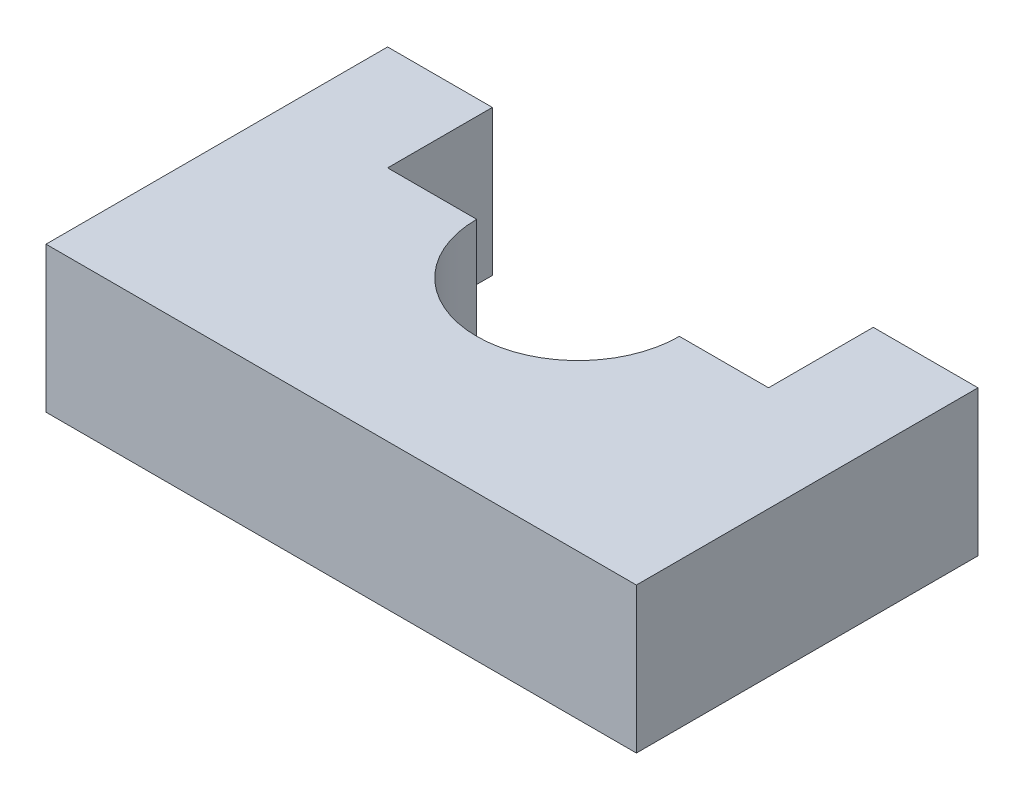
SolidWorks part; units mm, degrees
ref_plane "Front Plane" through (0, 0, 0) normal (0, 0, 1) x (1, 0, 0)
ref_plane "Top Plane" through (0, 0, 0) normal (0, 1, 0) x (1, 0, 0)
ref_plane "Right Plane" through (0, 0, 0) normal (1, 0, 0) x (0, 0, -1)
sketch "Sketch4" plane through (0, 0, 0) normal (0, 1, 0) x (1, 0, 0)
  line L0 (-30.4225, 0) -> (30.4225, 0)
  line L1 (30.4225, 0) -> (30.4225, 35.2066)
  line L3 (-30.4225, 0) -> (-30.4225, 35.2066)
  line L4 (-30.4225, 35.2066) -> (-19.6274, 35.2066)
  line L5 (30.4225, 35.2066) -> (19.6274, 35.2066)
  line L6 (-19.6274, 35.2066) -> (-19.6274, 24.4116)
  line L7 (-19.6274, 24.4116) -> (-10.4465, 24.4116)
  line L8 (19.6274, 24.4116) -> (19.6274, 35.2066)
  line L9 (10.4465, 24.4116) -> (19.6274, 24.4116)
  arc A0 (-10.4465, 24.4116) -> (10.4465, 24.4116) centre (0, 24.4116) ccw
  point P4 (0, 0)
extrude "Boss-Extrude1" add sketch "Sketch4" along normal blind 15
